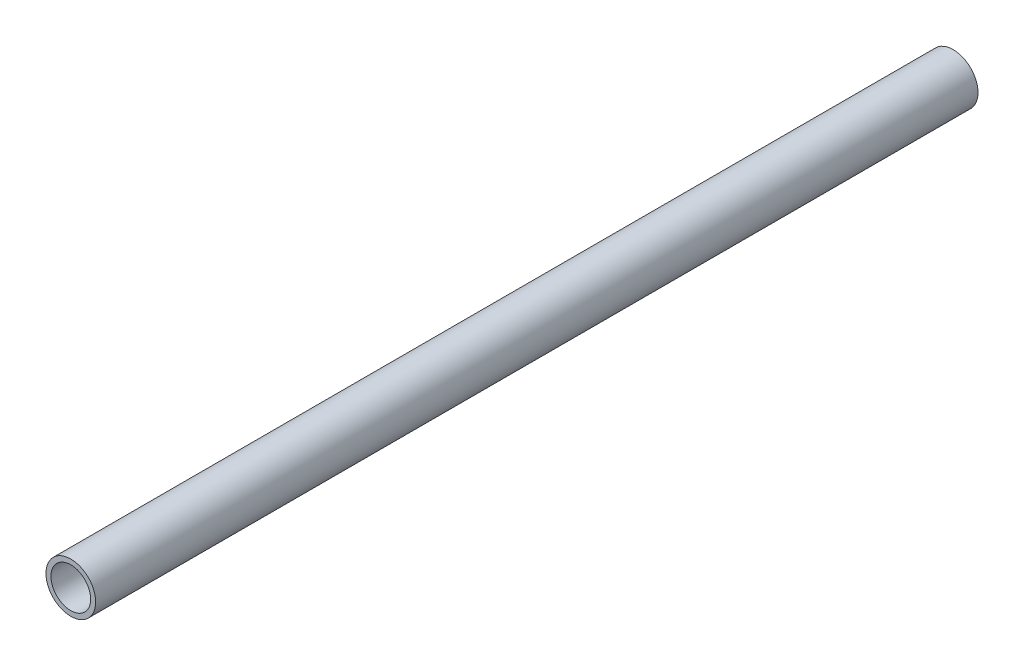
SolidWorks part; units mm, degrees
material "Thornel Mat VMA"
ref_plane "Front Plane" through (0, 0, 0) normal (0, 0, 1) x (1, 0, 0)
ref_plane "Top Plane" through (0, 0, 0) normal (0, 1, 0) x (1, 0, 0)
ref_plane "Right Plane" through (0, 0, 0) normal (1, 0, 0) x (0, 0, -1)
sketch "Sketch1" plane through (0, 0, 0) normal (0, 0, 1) x (1, 0, 0)
  circle A0 centre (0, 0) radius 5
  circle A1 centre (0, 0) radius 4
  dimension "D1" = 10
  dimension "D2" = 8
extrude "Boss-Extrude1" add sketch "Sketch1" along normal blind 177.6501
